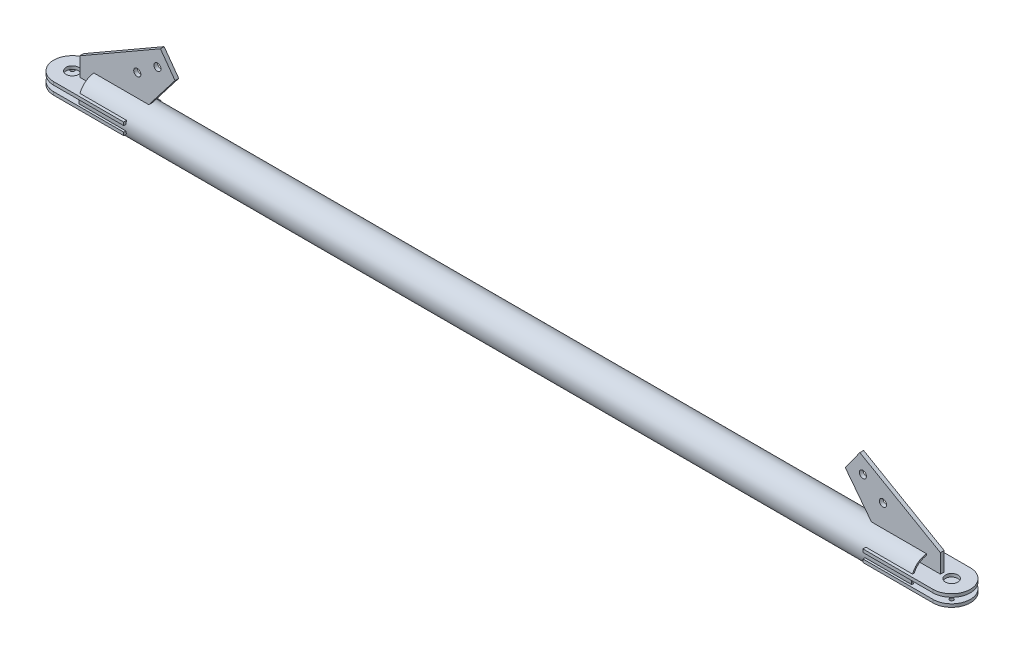
SolidWorks part; units mm, degrees
ref_plane "前视基准面" through (0, 0, 0) normal (0, 0, 1) x (1, 0, 0)
ref_plane "上视基准面" through (0, 0, 0) normal (0, 1, 0) x (1, 0, 0)
ref_plane "右视基准面" through (0, 0, 0) normal (1, 0, 0) x (0, 0, -1)
sketch "草图1" plane through (0, 0, 0) normal (1, 0, 0) x (0, 0, -1)
  circle A0 centre (0, 0) radius 54
  circle A1 centre (0, 0) radius 49
  dimension "D1" = 108
  dimension "D2" = 98
extrude "凸台-拉伸1" add sketch "草图1" along normal blind 2676.0311
ref_plane "基准面1" through (0, 0, 60) normal (0, 0, 1) x (1, 0, 0)
sketch "草图2" plane through (0, 0, 60) normal (0, 0, 1) x (1, 0, 0)
  line L0 (-1000, 0) -> (49000, 0) construction
  line L1 (-135, 19) -> (150, 19)
  line L2 (-135, 19) -> (-135, 9)
  line L3 (-135, 9) -> (150, 9)
  line L4 (150, 19) -> (150, 9)
  line L5 (-135, -9) -> (150, -9)
  line L6 (-135, -9) -> (-135, -19)
  line L7 (-135, -19) -> (150, -19)
  line L8 (150, -9) -> (150, -19)
  dimension "D1" = 10
  dimension "D2" = 150
  dimension "D3" = 285
  dimension "D4" = 9
  dimension "D5" = 9
extrude "凸台-拉伸2" add sketch "草图2" against normal blind 120 separate body
sketch "草图3" plane through (0, 19, 0) normal (0, 1, 0) x (1, 0, 0)
  line L0 (-135, 60) -> (-135, -60) construction
  line L1 (150, 60) -> (-135, 60) construction
  line L2 (-135, 0) -> (-135, 60)
  line L3 (-135, 60) -> (-75, 60)
  arc A0 (-135, 0) -> (-75, 60) centre (-75, 0) cw
  dimension "D1" = 60
extrude "切除-拉伸1" cut sketch "草图3" against normal through all
sketch "草图4" plane through (0, 19, 0) normal (0, 1, 0) x (1, 0, 0)
  line L0 (-155.1, -60) -> (155.1, -60) construction
  line L1 (-135, 0) -> (-135, -60)
  line L2 (-135, 0) -> (-135, -60) construction
  line L3 (-135, -60) -> (-75, -60)
  arc A0 (-135, 0) -> (-75, -60) centre (-75, 0) ccw
  dimension "D1" = 60
extrude "切除-拉伸2" cut sketch "草图4" against normal through all
sketch "草图5" plane through (0, 19, 0) normal (0, 1, 0) x (1, 0, 0)
  line L0 (-1075, 0) -> (48925, 0) construction
  line L1 (-75, -1000) -> (-75, 49000) construction
  circle A0 centre (-75, 0) radius 20
  dimension "D1" = 40
extrude "切除-拉伸3" cut sketch "草图5" against normal through all
sketch "草图8" plane through (0, -19, 0) normal (0, -1, 0) x (1, 0, 0)
  line L0 (-1075, 0) -> (48925, 0) construction
  line L1 (-75, -1000) -> (-75, 49000) construction
  circle A0 centre (-105, 30) radius 6
  circle A1 centre (-105, -30) radius 6
  dimension "D1" = 12
  dimension "D2" = 30
  dimension "D3" = 30
  dimension "D4" = 30
  dimension "D5" = 30
extrude "切除-拉伸4" cut sketch "草图8" against normal blind 10
ref_plane "基准面3" through (0, 0, -6) normal (0, 0, 1) x (1, 0, 0)
sketch "草图11" plane through (0, 0, -6) normal (0, 0, 1) x (1, 0, 0)
  line L0 (150, 19) -> (-45, 19)
  line L1 (150, 19) -> (-75, 19) construction
  line L2 (-45, 19) -> (-45, 79)
  line L3 (-45, 79) -> (214, 228)
  line L4 (214, 228) -> (261, 163)
  line L5 (261, 163) -> (150, 19)
  dimension "D1" = 195
  dimension "D2" = 60
  dimension "D3" = 259
  dimension "D4" = 209
  dimension "D5" = 144
  dimension "D6" = 306
extrude "凸台-拉伸4" add sketch "草图11" along normal blind 12
sketch "草图12" plane through (0, 0, -6) normal (0, 0, -1) x (-1, 0, 0)
  line L0 (-1000, 0) -> (49000, 0) construction
  line L1 (31.5, 0) -> (-968.5, 730) construction
  circle A0 centre (-204.3446, 172.1666) radius 11.5
  circle A1 centre (-139.7296, 124.9976) radius 11.5
  dimension "D4" = 23
  dimension "D1" = 31.5
  dimension "D2" = 1000
  dimension "D3" = 730
  dimension "D5" = 80
  dimension "D6" = 212
extrude "切除-拉伸5" cut sketch "草图12" against normal through all
ref_plane "基准面4" through (1338.0156, 0, 0) normal (1, 0, 0) x (0, 0, -1)
mirror "镜向2" about plane through (1338.0156, 0, 0) normal (1, 0, 0) of "切除-拉伸5", "凸台-拉伸4", "切除-拉伸4", "切除-拉伸3", "切除-拉伸1", "切除-拉伸2", "凸台-拉伸2"
